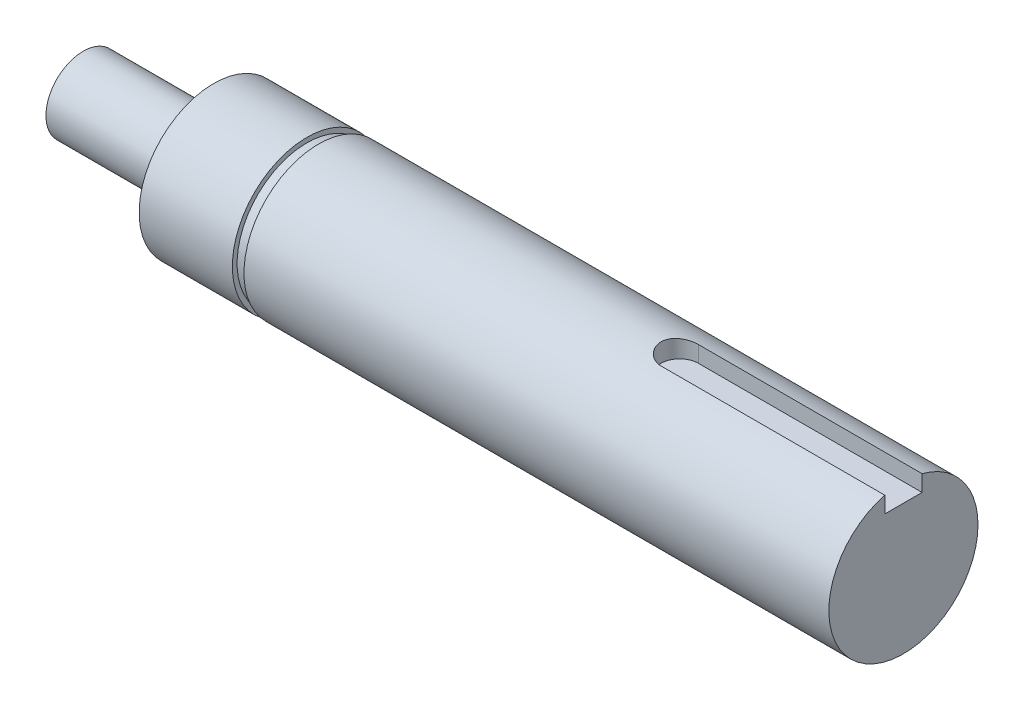
SolidWorks part; units mm, degrees
ref_plane "Front Plane" through (0, 0, 0) normal (0, 0, 1) x (1, 0, 0)
ref_plane "Top Plane" through (0, 0, 0) normal (0, 1, 0) x (1, 0, 0)
ref_plane "Right Plane" through (0, 0, 0) normal (1, 0, 0) x (0, 0, -1)
sketch "Sketch1" plane through (0, 0, 0) normal (0, 0, 1) x (1, 0, 0)
  line L0 (0, 0) -> (-177.5404, 0) construction
  line L1 (-69.85, 0) -> (-69.85, 3.175)
  line L2 (-69.85, 3.175) -> (-58.7375, 3.175)
  line L3 (-58.7375, 3.175) -> (-58.7375, 6.35)
  line L4 (-58.7375, 6.35) -> (-50.8, 6.35)
  line L5 (0, 6.35) -> (0, 0)
  line L6 (-69.85, 0) -> (0, 0)
  line L7 (-50.8, 6.35) -> (-50.8, 5.9436)
  line L8 (-50.8, 5.9436) -> (-49.8094, 5.9436)
  line L9 (-49.8094, 5.9436) -> (-49.8094, 6.35)
  line L10 (-49.8094, 6.35) -> (0, 6.35)
  dimension "D1" = 12.7
  dimension "D2" = 6.35
  dimension "D3" = 11.1125
  dimension "D4" = 69.85
  dimension "D5" = 11.8872
  dimension "D6" = 0.9906
  dimension "D7" = 7.9375
revolve "Revolve1" add sketch "Sketch1" angle 360 about L0
ref_plane "Plane1" through (0, 6.35, 0) normal (0, 1, 0) x (-1, 0, 0)
sketch "Sketch2" plane through (0, 6.35, 0) normal (0, 1, 0) x (-1, 0, 0)
  line L0 (19.05, 1.5875) -> (0, 1.5875)
  line L1 (0, 6.35) -> (0, -6.35) construction
  line L2 (0, 1.5875) -> (0, -1.5875)
  line L3 (0, -1.5875) -> (19.05, -1.5875)
  arc A0 (19.05, -1.5875) -> (19.05, 1.5875) centre (19.05, 0) ccw
  dimension "D1" = 3.175
  dimension "D2" = 19.05
extrude "Cut-Extrude1" cut sketch "Sketch2" against normal blind 1.5875
